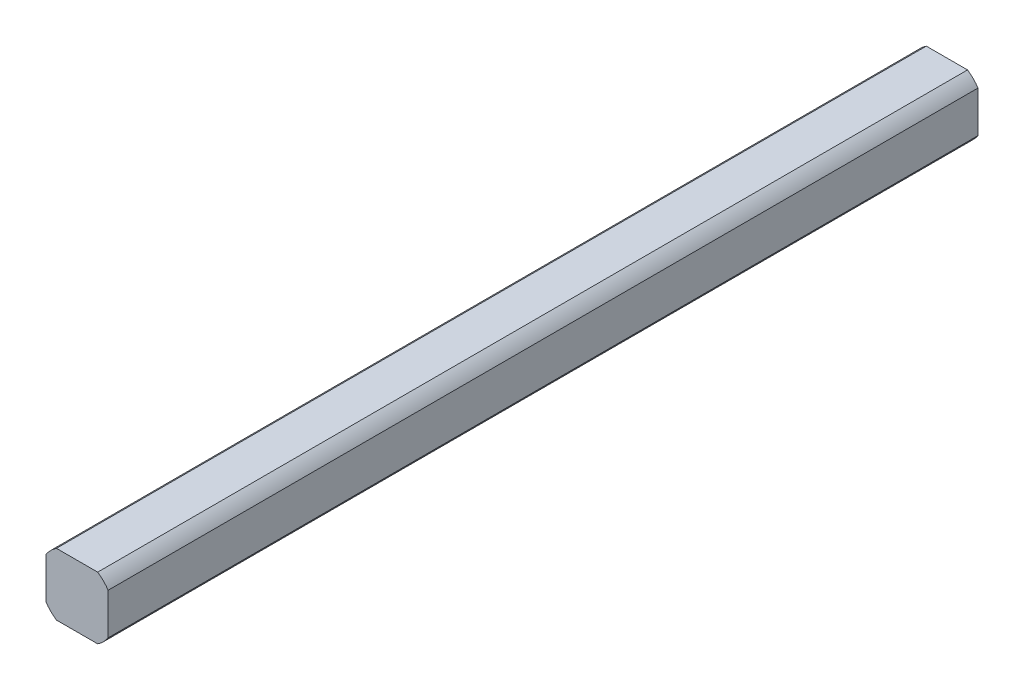
SolidWorks part; units mm, degrees
ref_plane "Front Plane" through (0, 0, 0) normal (0, 0, 1) x (1, 0, 0)
ref_plane "Top Plane" through (0, 0, 0) normal (0, 1, 0) x (1, 0, 0)
ref_plane "Right Plane" through (0, 0, 0) normal (1, 0, 0) x (0, 0, -1)
ref_plane "Plane1" through (0, 0, -54.3915) normal (0, 0, -1) x (-1, 0, 0)
sketch "Sketch4" plane through (0, 0, 0) normal (1, 0, 0) x (0, 0, -1)
  line L0 (54.3915, -14.4596) -> (54.3915, 14.4596) construction
  line L1 (-34.5085, -3.175) -> (54.3915, -3.175)
  line L2 (-34.5085, -3.175) -> (-34.5085, 3.175)
  line L3 (-34.5085, 3.175) -> (54.3915, 3.175)
  line L4 (54.3915, -3.175) -> (54.3915, 3.175)
  point P0 (0, 0)
  point P8 (0, 0)
  dimension "D1" = 6.35
  dimension "D2" = 88.9
  dimension "D3" = 3.175
extrude "Boss-Extrude1" add sketch "Sketch4" along normal mid plane 6.35
sketch "Sketch6" plane through (0, 0, 34.5085) normal (0, 0, 1) x (1, 0, 0)
  circle A0 centre (0, 0) radius 3.81
  dimension "D1" = 7.62
extrude "Cut-Extrude3" cut sketch "Sketch6" against normal through all flip side to cut
sketch "Sketch7" plane through (0, 0, -54.3915) normal (0, 0, -1) x (-1, 0, 0)
  circle A0 centre (0, 0) radius 3.81
  circle A1 centre (0, 0) radius 3.81 construction
